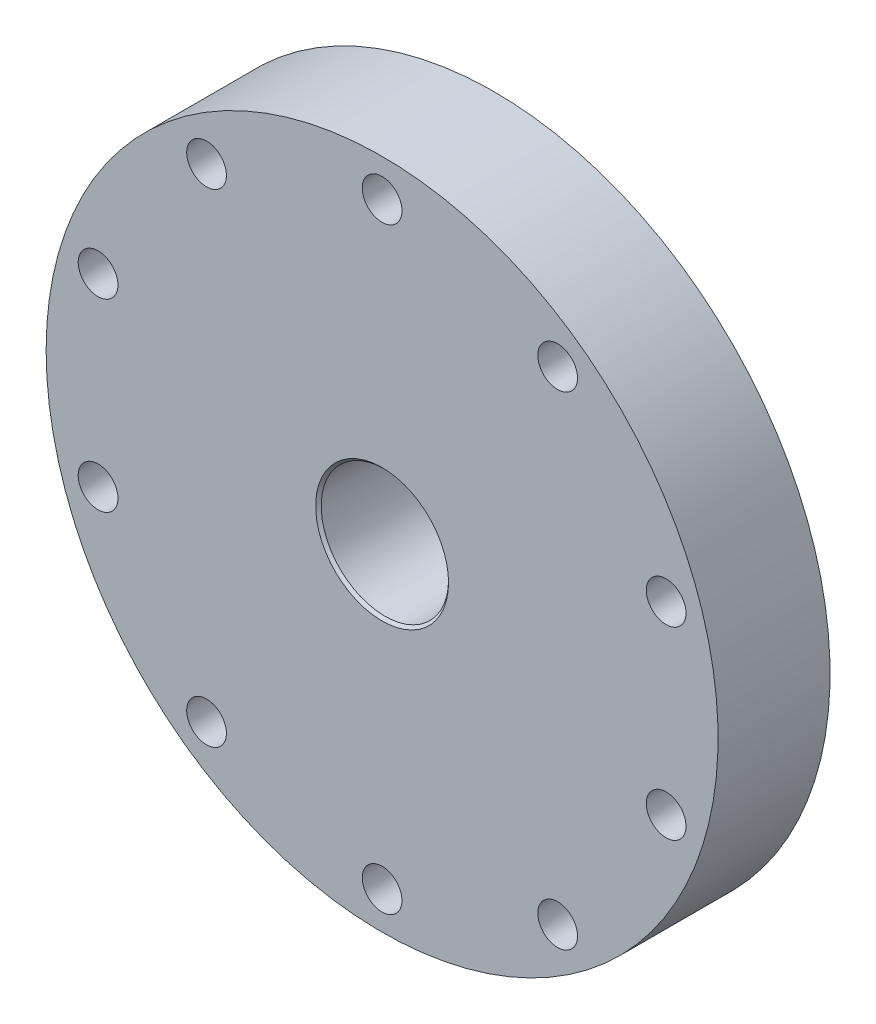
SolidWorks part; units mm, degrees
material "AISI Type 316L stainless steel"
ref_plane "Front Plane" through (0, 0, 0) normal (0, 0, 1) x (1, 0, 0)
ref_plane "Top Plane" through (0, 0, 0) normal (0, 1, 0) x (1, 0, 0)
ref_plane "Right Plane" through (0, 0, 0) normal (1, 0, 0) x (0, 0, -1)
sketch "Sketch1" plane through (0, 0, 0) normal (0, 0, 1) x (1, 0, 0)
  circle A0 centre (0, 0) radius 57.15
  point P19 (0, 0)
  dimension "D1" = 114.3
extrude "Boss-Extrude1" add sketch "Sketch1" along normal blind 19.05
sketch "Hole Alignment" plane through (0, 0, 19.05) normal (0, 0, 1) x (1, 0, 0)
  circle A0 centre (0, 0) radius 50.8 construction
  point P7 (29.8595, 41.0981)
  point P12 (0, 0)
  point P13 (48.3137, 15.6981)
  point P14 (48.3137, -15.6981)
  point P15 (29.8595, -41.0981)
  point P16 (0, -50.8)
  point P17 (-29.8595, -41.0981)
  point P18 (-48.3137, -15.6981)
  point P19 (-48.3137, 15.6981)
  point P20 (0, 50.8)
  point P21 (-29.8595, 41.0981)
  point P22 (0, 0)
  dimension "D1" = 101.6
  dimension "D2" = 10
hole_wizard "1/4 Clearance Hole1" positions "Sketch4" profile "Sketch5" hole size "1/4" standard "ANSI Inch"
sketch "Sketch4" plane through (0, 0, 19.05) normal (0, 0, 1) x (1, 0, 0)
  point P32 (0, 50.8)
  point P35 (29.8595, 41.0981)
  point P38 (48.3137, 15.6981)
  point P41 (48.3137, -15.6981)
  point P44 (29.8595, -41.0981)
  point P47 (0, -50.8)
  point P50 (-29.8595, -41.0981)
  point P53 (-48.3137, -15.6981)
  point P56 (-48.3137, 15.6981)
  point P59 (-29.8595, 41.0981)
sketch "Sketch5" plane through (0, 50.8, 19.05) normal (1, 0, 0) x (0, -1, 0)
  line L0 (0, 0) -> (0, 59.1798)
  line L1 (0, 59.1798) -> (3.3782, 57.15)
  line L2 (3.3782, 57.15) -> (3.3782, 0)
  line L5 (3.3782, 0) -> (0, 0)
  line L10 (0, 59.1798) -> (-3.3782, 57.15) construction
  line L11 (0, -6.35) -> (0, 107.95) construction
  dimension "Hole Dia." = 6.7564
  dimension "Hole Depth" = 57.15
  dimension "Drill Angle" = 118
sketch "Sketch9" plane through (0, 0, 0) normal (0, 0, -1) x (-1, 0, 0)
  circle A0 centre (0, 0) radius 44.45
  dimension "D1" = 88.9
extrude "Pipe AlignmentSeal" add sketch "Sketch9" along normal blind 2.3813
hole_wizard "1/2 NPT Tapped Hole6" positions "Sketch17" profile "Sketch14" size "1/2" standard "ANSI Inch" end condition through all
sketch "Sketch17" plane through (0, 0, 19.05) normal (0, 0, 1) x (1, 0, 0)
  point P0 (0, 0)
sketch "Sketch14" plane through (0, 0, 19.05) normal (1, 0, 0) x (0, -1, 0)
  line L0 (0, 0) -> (0, 21.4313)
  line L1 (0, 21.4313) -> (9.5631, 21.4313)
  line L2 (9.5631, 21.4313) -> (8.9281, 20.7963)
  line L3 (8.9281, 20.7963) -> (8.9281, 19.05)
  line L4 (8.9281, 19.05) -> (10.2758, 19.05)
  line L5 (10.2758, 19.05) -> (10.832, 0.471)
  line L6 (10.832, 0.471) -> (11.303, 0)
  line L7 (11.303, 0) -> (0, 0)
  line L8 (0, -6.35) -> (0, 107.95) construction
  line L9 (-10.832, 0.471) -> (-11.303, 0) construction
  line L10 (-9.5631, 21.4313) -> (-8.9281, 20.7963) construction
  line L11 (-8.9281, 19.05) -> (-10.2758, 19.05) construction
  line L12 (-10.2758, 19.05) -> (-10.832, 0.471) construction
  dimension "Thru Tap Drill Dia." = 17.8562
  dimension "Thru Tap Drill Depth" = 21.4313
  dimension "Thread Dia." = 21.6641
  dimension "Thread Angle" = 3.43
  dimension "Thread Depth" = 19.05
  dimension "Near C'Sink Dia." = 22.606
  dimension "Near C'Sink Angle" = 90
  dimension "Far C'Sink Dia." = 19.1262
  dimension "Far C'Sink Angle" = 90
